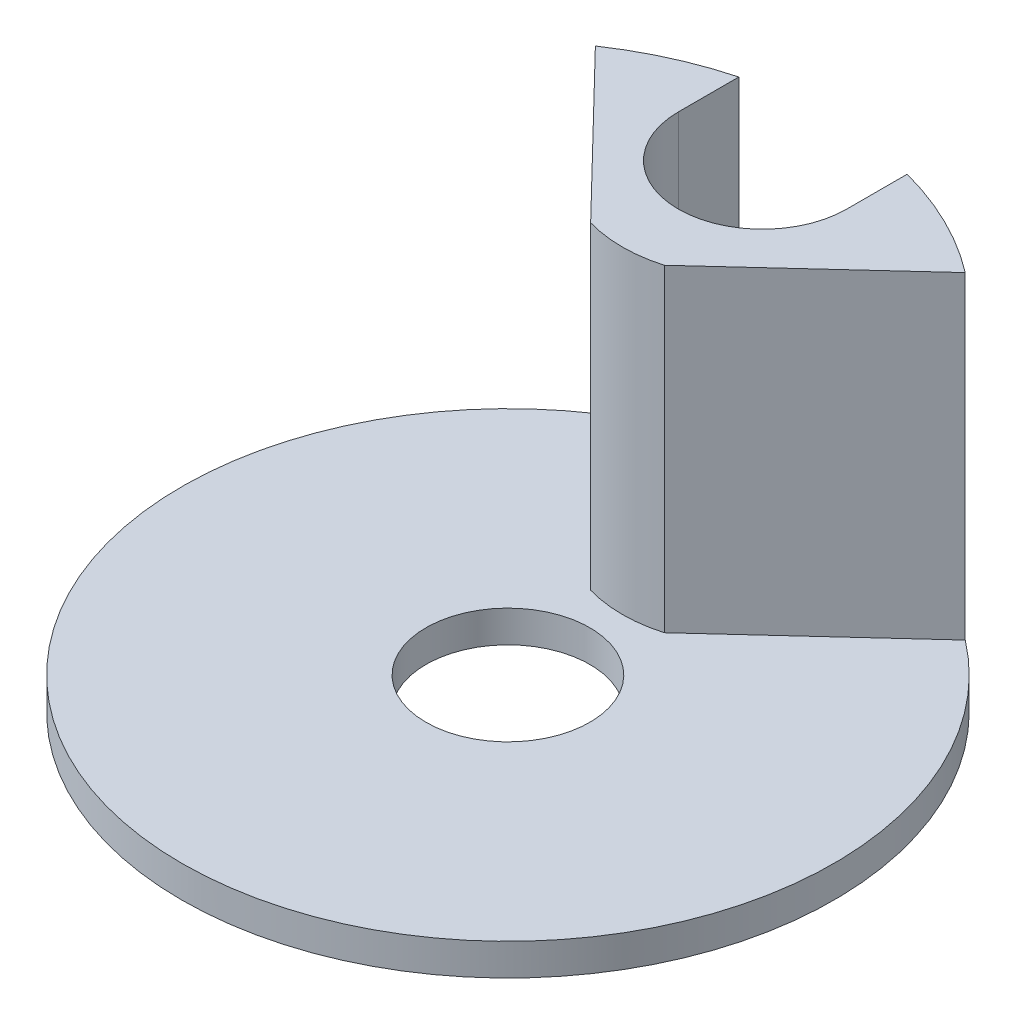
SolidWorks part; units mm, degrees
ref_plane "Front Plane" through (0, 0, 0) normal (0, 0, 1) x (1, 0, 0)
ref_plane "Top Plane" through (0, 0, 0) normal (0, 1, 0) x (1, 0, 0)
ref_plane "Right Plane" through (0, 0, 0) normal (1, 0, 0) x (0, 0, -1)
sketch "Sketch1" plane through (0, 0, 0) normal (0, 1, 0) x (1, 0, 0)
  circle A0 centre (0, 0) radius 20.5
  dimension "D1" = 41
extrude "Boss-Extrude1" add sketch "Sketch1" along normal blind 2
sketch "Sketch2" plane through (0, 2, 0) normal (0, 1, 0) x (1, 0, 0)
  circle A0 centre (0, 0) radius 5.15
  dimension "D1" = 10.3
extrude "Cut-Extrude1" cut sketch "Sketch2" against normal blind 3
sketch "Sketch3" plane through (0, 2, 0) normal (0, 1, 0) x (1, 0, 0)
  circle A0 centre (0, 16) radius 2
  dimension "D2" = 4
  dimension "D1" = 16
extrude "Cut-Extrude2" cut sketch "Sketch3" against normal blind 2
sketch "Sketch4" plane through (0, 2, 0) normal (0, 1, 0) x (1, 0, 0)
  line L0 (-2.0146, 7.2145) -> (-11.4847, 16.9809)
  line L1 (2.6135, 7.2145) -> (12.47, 16.2711)
  line L2 (-5.2903, 16) -> (-5.2903, 19.8024)
  line L3 (5.2903, 16) -> (5.2903, 19.802)
  arc A0 (-11.4847, 16.9809) -> (-5.2903, 19.8024) centre (-0.0006, -0.0215) cw
  circle A1 centre (0, 0) radius 20.5 construction
  arc A2 (-2.0146, 7.2145) -> (2.6135, 7.2145) centre (0.2995, 15.2511) ccw
  arc A3 (-5.2903, 16) -> (5.2903, 16) centre (0, 16) ccw
  arc A4 (5.2903, 19.802) -> (12.47, 16.2711) centre (-0.0006, -0.0215) cw
  point P12 (-2.5855, 9.014)
  point P13 (2.8741, 9.014)
  point P15 (3.1887, 8.1067)
  point P17 (-2.4377, 8.1067)
  point P18 (-4.2757, 16)
  point P19 (0, 0)
  point P20 (0, 0)
  point P21 (0, 0)
  point P22 (0, 0)
  point P23 (0, 0)
  point P24 (-5.2903, 16)
  point P25 (-2.0146, 7.2145)
  point P26 (2.6135, 7.2145)
extrude "Boss-Extrude4" add sketch "Sketch4" along normal blind 20
